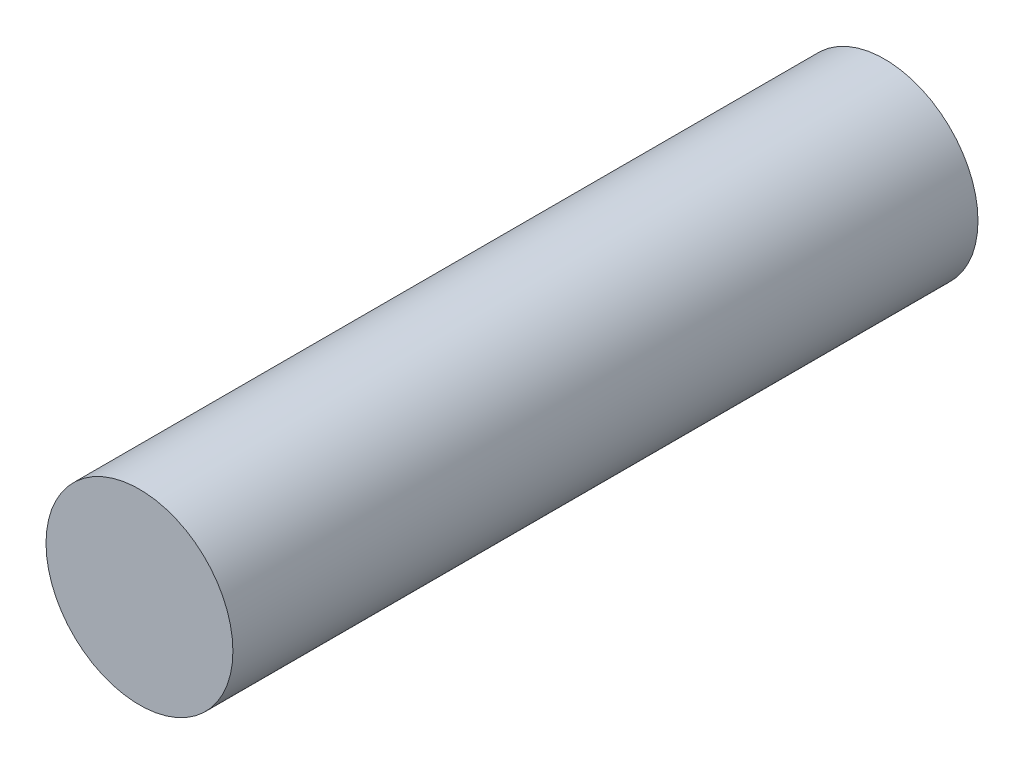
SolidWorks part; units mm, degrees
ref_plane "Front Plane" through (0, 0, 0) normal (0, 0, 1) x (1, 0, 0)
ref_plane "Top Plane" through (0, 0, 0) normal (0, 1, 0) x (1, 0, 0)
ref_plane "Right Plane" through (0, 0, 0) normal (1, 0, 0) x (0, 0, -1)
sketch "Sketch1" plane through (0, 0, 0) normal (0, 0, 1) x (1, 0, 0)
  circle A0 centre (0, 52.2816) radius 4.7786
extrude "Boss-Extrude1" add sketch "Sketch1" against normal up to surface (38.1 mm away) contours A0
